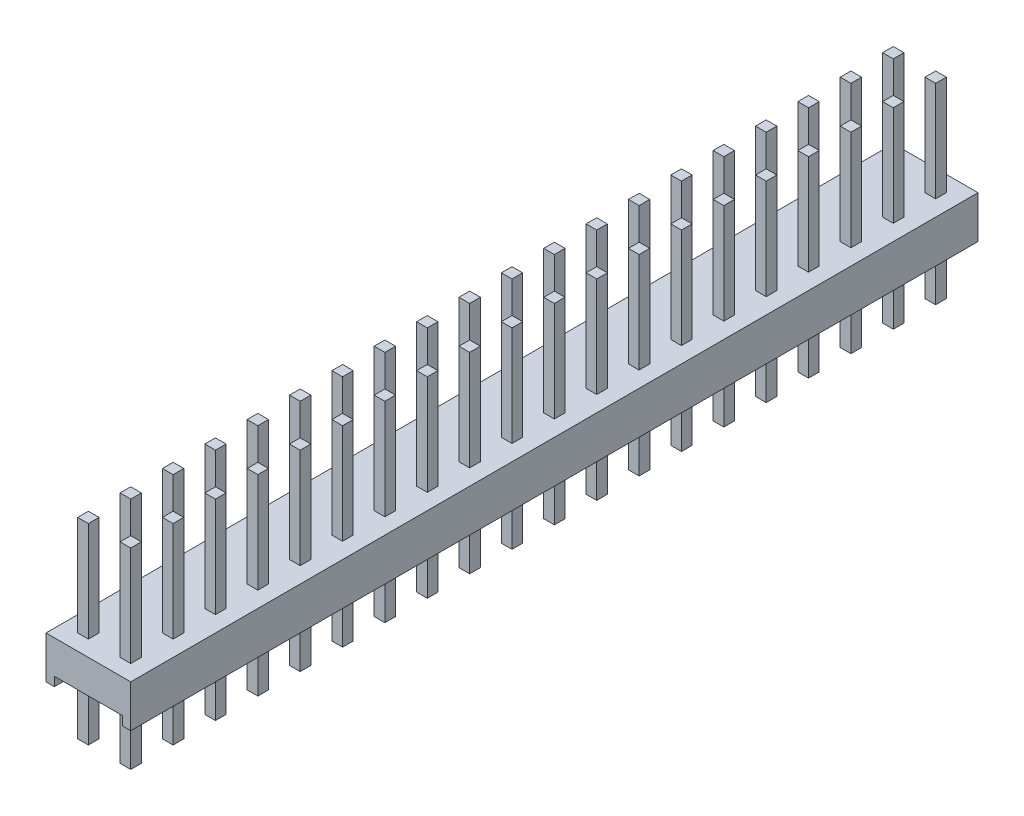
SolidWorks part; units mm, degrees
ref_plane "Спереди" through (0, 0, 0) normal (0, 0, 1) x (1, 0, 0)
ref_plane "Сверху" through (0, 0, 0) normal (0, 1, 0) x (1, 0, 0)
ref_plane "Справа" through (0, 0, 0) normal (1, 0, 0) x (0, 0, -1)
sketch "Эскиз1" plane through (0, 0, 0) normal (0, 0, 1) x (1, 0, 0)
  line L0 (-2.54, 0) -> (-2.54, 2.54)
  line L1 (-2.54, 2.54) -> (2.54, 2.54)
  line L2 (2.54, 2.54) -> (2.54, 0)
  line L3 (-2.54, 0) -> (-2.04, 0)
  line L4 (-2.04, 0) -> (-2.04, 0.54)
  line L5 (-2.04, 0.54) -> (2.04, 0.54)
  line L6 (2.04, 0.54) -> (2.04, 0)
  line L7 (2.04, 0) -> (2.54, 0)
  line L8 (-2.54, 0) -> (2.54, 0) construction
  dimension "D1" = 2.54
  dimension "D2" = 5.08
  dimension "D3" = 0.5
  dimension "D4" = 0.54
  dimension "D5" = 0.5
  dimension "D6" = 2.54
extrude "Бобышка-Вытянуть1" add sketch "Эскиз1" along normal blind 2.54
sketch "Эскиз2" plane through (0, 2.54, 0) normal (0, 1, 0) x (1, 0, 0)
  line L0 (-2.54, -1.27) -> (2.54, -1.27) construction
  line L1 (-1.59, -0.95) -> (-0.95, -0.95)
  line L2 (-1.59, -0.95) -> (-1.59, -1.59)
  line L3 (-1.59, -1.59) -> (-0.95, -1.59)
  line L4 (-0.95, -0.95) -> (-0.95, -1.59)
  line L5 (0.95, -0.95) -> (1.59, -0.95)
  line L6 (0.95, -0.95) -> (0.95, -1.59)
  line L7 (0.95, -1.59) -> (1.59, -1.59)
  line L8 (1.59, -0.95) -> (1.59, -1.59)
  line L9 (-2.54, -2.54) -> (-2.54, 0) construction
  line L12 (0, 0) -> (0, -2.54) construction
  line L13 (2.54, -2.54) -> (-2.54, -2.54) construction
  line L14 (2.54, -2.54) -> (2.54, 0) construction
  line L15 (-1.27, -1.59) -> (-1.27, -0.95) construction
  line L16 (1.27, -0.95) -> (1.27, -1.59) construction
  dimension "D1" = 0.64
  dimension "D2" = 2.54
extrude "Бобышка-Вытянуть2" add sketch "Эскиз2" along normal blind 6 and the other way blind 5.5
pattern_linear "Линейный массив27" count 20 spacing 2.54 along (0, 0, -1) of "Бобышка-Вытянуть1", "Бобышка-Вытянуть2"
